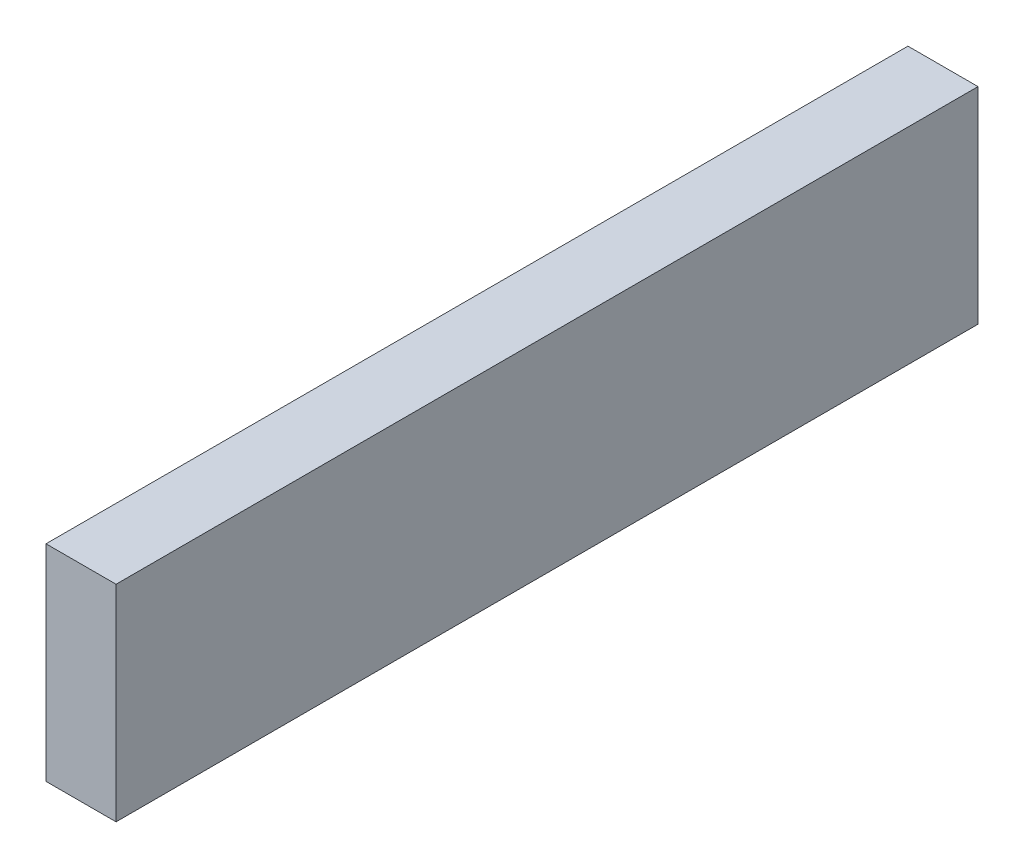
SolidWorks part; units mm, degrees
ref_plane "Front Plane" through (0, 0, 0) normal (0, 0, 1) x (1, 0, 0)
ref_plane "Top Plane" through (0, 0, 0) normal (0, 1, 0) x (1, 0, 0)
ref_plane "Right Plane" through (0, 0, 0) normal (1, 0, 0) x (0, 0, -1)
sketch "Sketch1" plane through (0, 0, 0) normal (0, 0, 1) x (1, 0, 0)
  line L1 (10.16, 29.845) -> (-10.16, 29.845)
  line L2 (10.16, 29.845) -> (10.16, -29.845)
  line L3 (10.16, -29.845) -> (-10.16, -29.845)
  line L4 (-10.16, 29.845) -> (-10.16, -29.845)
  line L5 (10.16, 29.845) -> (-10.16, -29.845) construction
  line L6 (10.16, -29.845) -> (-10.16, 29.845) construction
  point P0 (0, 0)
  dimension "D1" = 20.32
  dimension "D2" = 59.69
extrude "Boss-Extrude1" add sketch "Sketch1" along normal blind 250
